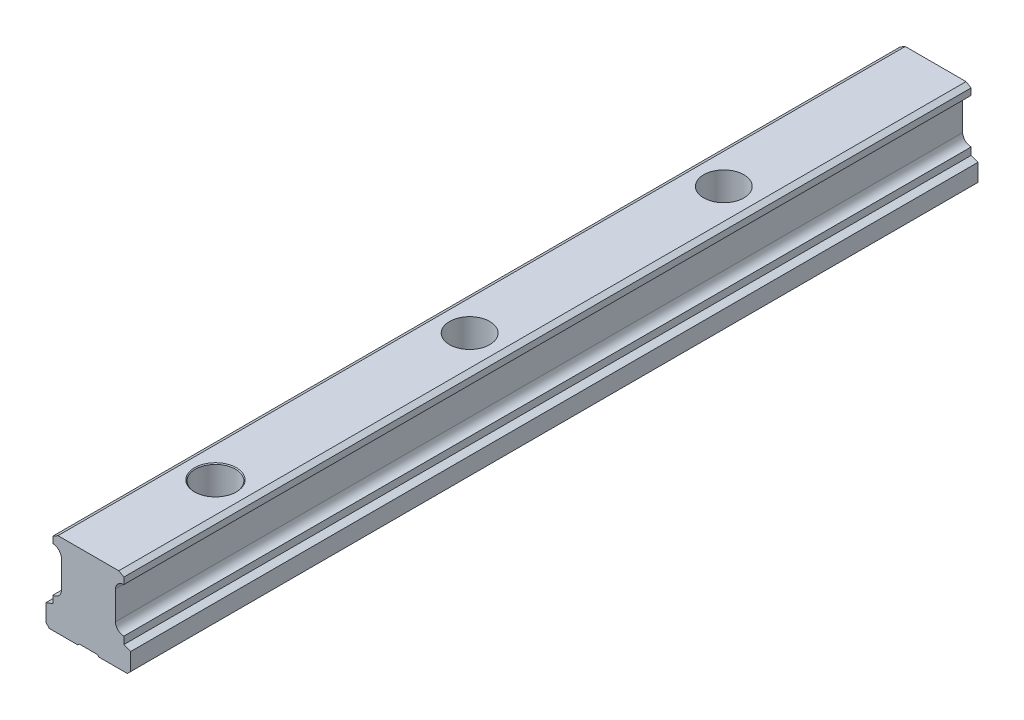
SolidWorks part; units mm, degrees
ref_plane "Plan de face" through (0, 0, 0) normal (0, 0, 1) x (1, 0, 0)
ref_plane "Plan de dessus" through (0, 0, 0) normal (0, 1, 0) x (1, 0, 0)
ref_plane "Plan de droite" through (0, 0, 0) normal (1, 0, 0) x (0, 0, -1)
ref_plane "Plan1" through (0, 0, 0) normal (0, 0, -1) x (-1, 0, 0)
sketch "Esquisse1" plane through (0, 0, 0) normal (0, 0, -1) x (-1, 0, 0)
  line L0 (-19.2, 7.9737) -> (-19.2, 0)
  line L1 (-19.2, 0) -> (0.8, 0)
  line L2 (0.8, 0) -> (0.8, 20)
  line L3 (0.8, 20) -> (-17.575, 20)
  line L4 (-17.575, 20) -> (-17.575, 17.7671)
  line L5 (-15.5625, 15.8524) -> (-15.5625, 9.1476)
  arc A0 (-15.5625, 9.1476) -> (-19.2, 7.9737) centre (-17.6174, 9.2924) cw
  arc A1 (-17.575, 17.7671) -> (-15.5625, 15.8524) centre (-17.6174, 15.7076) cw
extrude "Boss.-Extru.1" add sketch "Esquisse1" against normal blind 1980
sketch "Esquisse2" plane through (0, 0, 1980) normal (0, 0, 1) x (1, 0, 0)
  line L0 (17.575, 7.2329) -> (17.575, 4.9085)
  line L1 (17.575, 4.9085) -> (19.2, 4.9085)
  line L2 (19.2, 4.9085) -> (19.2, 7.9737)
  arc A0 (19.2, 7.9737) -> (17.575, 7.2329) centre (17.6174, 9.2924) cw
extrude "Enlèv. mat.-Extru.1" cut sketch "Esquisse2" against normal through all
sketch "Esquisse3" plane through (0, 0, 1980) normal (0, 0, 1) x (1, 0, 0)
  line L0 (7.05, 0) -> (11.35, 0)
  line L1 (11.35, 0) -> (11.35, 0.35)
  line L2 (11.35, 0.35) -> (7.05, 0.35)
  line L3 (7.05, 0.35) -> (7.05, 0)
extrude "Enlèv. mat.-Extru.2" cut sketch "Esquisse3" against normal blind 1980
sketch "Esquisse4" plane through (0, 0, 1980) normal (0, 0, 1) x (1, 0, 0)
  line L0 (-0.8, 5.5) -> (0.825, 5.5)
  line L1 (0.825, 5.5) -> (0.825, 20)
  line L2 (0.825, 20) -> (-0.8, 20)
  line L3 (-0.8, 20) -> (-0.8, 5.5)
extrude "Enlèv. mat.-Extru.3" cut sketch "Esquisse4" against normal through all
sketch "Esquisse5" plane through (0, 0, 1980) normal (0, 0, 1) x (1, 0, 0)
  line L0 (0.825, 17.7671) -> (0.825, 7.2329)
  line L1 (2.8375, 9.1476) -> (2.8375, 15.8524)
  arc A0 (0.825, 7.2329) -> (2.8375, 9.1476) centre (0.7826, 9.2924) ccw
  arc A1 (2.8375, 15.8524) -> (0.825, 17.7671) centre (0.7826, 15.7076) ccw
extrude "Enlèv. mat.-Extru.4" cut sketch "Esquisse5" against normal through all
draft "Dépouille1" type of draft neutral plane draft angle 20 faces to draft 1 face at (0.0125, 5.5, 990) neutral plane through (0.825, 5.5, 0) neutral plane normal (-1, 0, 0) parameters "D1"=20
draft "Dépouille2" type of draft neutral plane draft angle 20 faces to draft 1 face at (18.3875, 4.9085, 990) neutral plane through (19.2, 7.9737, 1980) neutral plane normal (1, 0, 0) parameters "D1"=20
draft "Dépouille3" type of draft neutral plane draft angle 45 faces to draft 2 face at (11.35, 0.175, 990) face at (7.05, 0.175, 990) neutral plane through (11.35, 0.35, 0) neutral plane normal (0, -1, 0) parameters "D1"=45
hole_wizard "Perçage1" positions "Esquisse7" profile "Esquisse6" legacy
sketch "Esquisse7" plane through (0, 20, 0) normal (0, 1, 0) x (1, 0, 0)
  point P0 (9.2, -30)
  point P1 (9.2, -90)
  point P2 (9.2, -150)
  point P3 (9.2, -210)
  point P4 (9.2, -270)
  point P5 (9.2, -330)
  point P6 (9.2, -390)
  point P7 (9.2, -450)
  point P8 (9.2, -510)
  point P9 (9.2, -570)
  point P10 (9.2, -630)
  point P11 (9.2, -690)
  point P12 (9.2, -750)
  point P13 (9.2, -810)
  point P14 (9.2, -870)
  point P15 (9.2, -930)
  point P16 (9.2, -990)
  point P17 (9.2, -1050)
  point P18 (9.2, -1110)
  point P19 (9.2, -1170)
  point P20 (9.2, -1230)
  point P21 (9.2, -1290)
  point P22 (9.2, -1350)
  point P23 (9.2, -1410)
  point P24 (9.2, -1470)
  point P25 (9.2, -1530)
  point P26 (9.2, -1590)
  point P27 (9.2, -1650)
  point P28 (9.2, -1710)
  point P29 (9.2, -1770)
  point P30 (9.2, -1830)
  point P31 (9.2, -1890)
  point P32 (9.2, -1950)
sketch "Esquisse6" plane through (9.2, 20, 30) normal (1, 0, 0) x (0, 0, 1)
  line L0 (0, 0) -> (0, 20)
  line L1 (0, 20) -> (3, 20)
  line L2 (3, 20) -> (3, 8.5)
  line L3 (3, 8.5) -> (4.75, 8.5)
  line L4 (4.75, 8.5) -> (4.75, 0)
  line L5 (4.75, 0) -> (0, 0)
  line L6 (0, 110) -> (0, -10) construction
  dimension "Diamètre" = 6
  dimension "Profondeur" = 20
  dimension "Diamètre chambrage" = 9.5
  dimension "Profondeur chambrage" = 8.5
chamfer "Chanfrein1" distance 0.8 angle 45 2 edges at (19.2, 0, 990) (-0.8, 0, 990)
chamfer "Chanfrein2" distance 1.2 angle 30 1 edges at (0.825, 20, 990)
chamfer "Chanfrein3" distance 0.2 angle 45 3 edges at (12.2, 0, 1950) (6.2, 0, 1950) (9.2, 20, 1954.75)
chamfer "Chanfrein4" distance 0.6928 angle 60 1 edges at (17.575, 20, 990)
ref_plane "Plan2" through (0, 0, 1980) normal (0, 0, 1) x (1, 0, 0)
sketch "Esquisse12" plane through (0, 0, 1980) normal (0, 0, 1) x (1, 0, 0)
  line L0 (-23.2139, 45.9286) -> (54.94, 45.9286)
  line L1 (-23.2139, 45.9286) -> (-23.2139, -28.586)
  line L2 (-23.2139, -28.586) -> (54.94, -28.586)
  line L3 (54.94, 45.9286) -> (54.94, -28.586)
extrude "Enlèv. mat.-Extru.5" cut sketch "Esquisse12" against normal through all from offset 200
